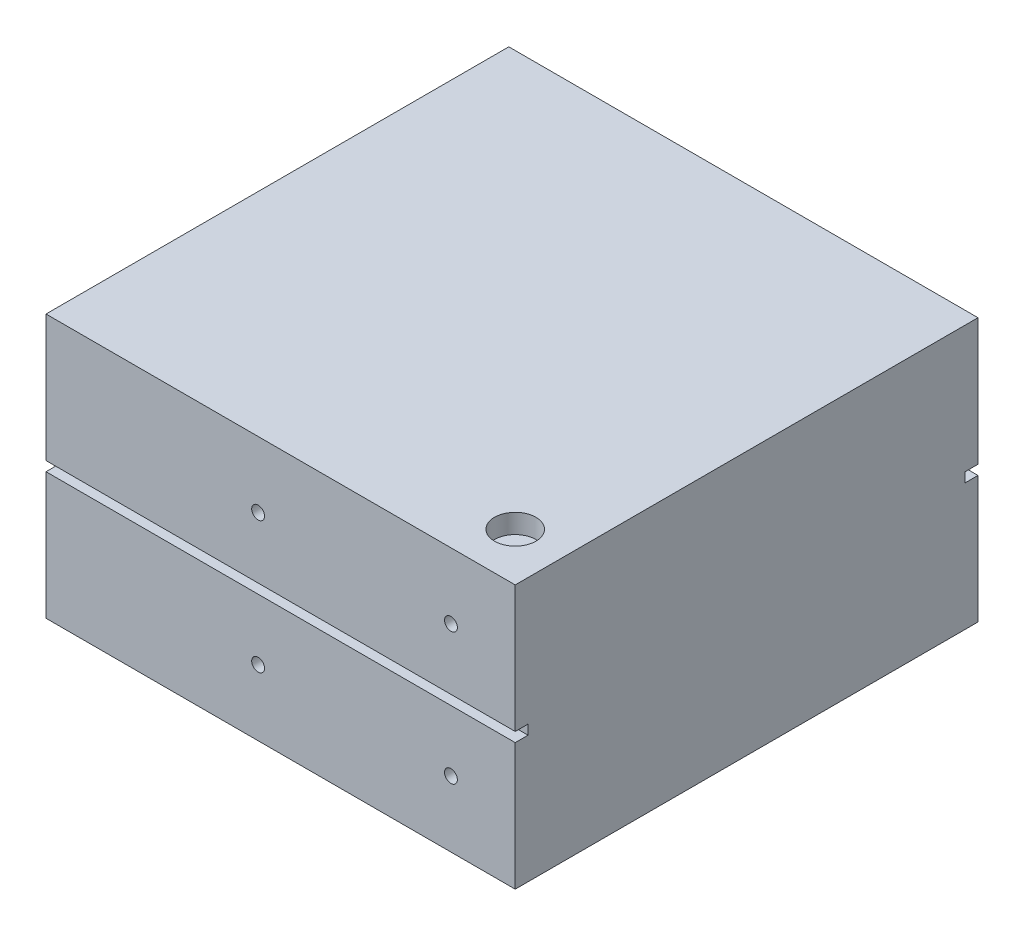
SolidWorks part; units mm, degrees
ref_plane "Front Plane" through (0, 0, 0) normal (0, 0, 1) x (1, 0, 0)
ref_plane "Top Plane" through (0, 0, 0) normal (0, 1, 0) x (1, 0, 0)
ref_plane "Right Plane" through (0, 0, 0) normal (1, 0, 0) x (0, 0, -1)
sketch "Sketch1" plane through (0, 0, 0) normal (0, 1, 0) x (1, 0, 0)
  line L1 (-56.6031, 36.8369) -> (89.3969, 36.8369)
  line L2 (-56.6031, 36.8369) -> (-56.6031, -107.1631)
  line L3 (-56.6031, -107.1631) -> (89.3969, -107.1631)
  line L4 (89.3969, 36.8369) -> (89.3969, -107.1631)
  dimension "D1" = 146
  dimension "D2" = 144
extrude "Boss-Extrude1" add sketch "Sketch1" along normal blind 82
shell "Shell1" thickness 6
sketch "Sketch2" plane through (0, 82, 0) normal (0, 1, 0) x (1, 0, 0)
  line L0 (89.3969, -107.1631) -> (89.3969, 36.8369) construction
  line L1 (-56.6031, -107.1631) -> (89.3969, -107.1631) construction
  circle A0 centre (74.3969, -92.1631) radius 6.45
  point P6 (76.2963, -90.4156)
  dimension "D1" = 15
  dimension "D2" = 15
extrude "Cut-Extrude1" cut sketch "Sketch2" against normal blind 10
sketch "Sketch3" plane through (-56.6031, 0, 0) normal (-1, 0, 0) x (0, 0, 1)
  line L0 (-36.8369, 0) -> (107.1631, 0) construction
  line L1 (-36.8369, 82) -> (-36.8369, 0) construction
  line L2 (107.1631, 82) -> (107.1631, 0) construction
  line L3 (-36.8369, 82) -> (107.1631, 82) construction
  circle A0 centre (87.1631, 62) radius 6.5
  circle A1 centre (-16.8369, 20) radius 6.5
  dimension "D1" = 20
  dimension "D2" = 20
  dimension "D3" = 20
  dimension "D4" = 20
extrude "Cut-Extrude2" cut sketch "Sketch3" against normal blind 5
sketch "Sketch4" plane through (-56.6031, 0, 0) normal (-1, 0, 0) x (0, 0, 1)
  line L0 (-36.8369, 82) -> (-36.8369, 0) construction
  line L1 (-36.8369, 42.5) -> (-32.8369, 42.5)
  line L2 (-36.8369, 42.5) -> (-36.8369, 39.5)
  line L3 (-36.8369, 39.5) -> (-32.8369, 39.5)
  line L4 (-32.8369, 42.5) -> (-32.8369, 39.5)
  line L5 (107.1631, 82) -> (107.1631, 0) construction
  line L6 (107.1631, 42.5) -> (103.1631, 42.5)
  line L7 (107.1631, 42.5) -> (107.1631, 39.5)
  line L8 (107.1631, 39.5) -> (103.1631, 39.5)
  line L9 (103.1631, 42.5) -> (103.1631, 39.5)
  line L10 (-36.8369, 82) -> (107.1631, 82) construction
  point P12 (-32.8369, 41)
  point P15 (103.1631, 41)
  dimension "D1" = 4
  dimension "D2" = 3
  dimension "D3" = 4
  dimension "D4" = 3
  dimension "D5" = 41
  dimension "D6" = 41
extrude "Cut-Extrude3" cut sketch "Sketch4" against normal through all
sketch "Sketch5" plane through (0, 0, 107.1631) normal (0, 0, 1) x (1, 0, 0)
  line L0 (-56.6031, 82) -> (89.3969, 82) construction
  line L1 (-56.6031, 0) -> (89.3969, 0) construction
  line L3 (89.3969, 82) -> (89.3969, 42.5) construction
  line L4 (89.3969, 39.5) -> (89.3969, 0) construction
  circle A0 centre (69.3969, 61.5) radius 2
  circle A1 centre (9.3969, 61.5) radius 2
  circle A2 centre (9.3969, 20.5) radius 2
  circle A3 centre (69.3969, 20.5) radius 2
  dimension "D1" = 20.5
  dimension "D2" = 20.5
  dimension "D3" = 20.5
  dimension "D4" = 20.5
  dimension "D5" = 20
  dimension "D6" = 20
  dimension "D7" = 60
  dimension "D8" = 60
extrude "Cut-Extrude4" cut sketch "Sketch5" against normal blind 4
sketch "Sketch6" plane through (0, 0, -36.8369) normal (0, 0, -1) x (-1, 0, 0)
  circle A0 centre (-9.3969, 61.5) radius 2
  circle A1 centre (-69.3969, 61.5) radius 2
  circle A2 centre (-69.3969, 20.5) radius 2
  circle A3 centre (-9.3969, 20.5) radius 2
  point P10 (-69.3969, 61.5)
  point P12 (-9.3969, 61.5)
extrude "Cut-Extrude5" cut sketch "Sketch6" against normal blind 4
